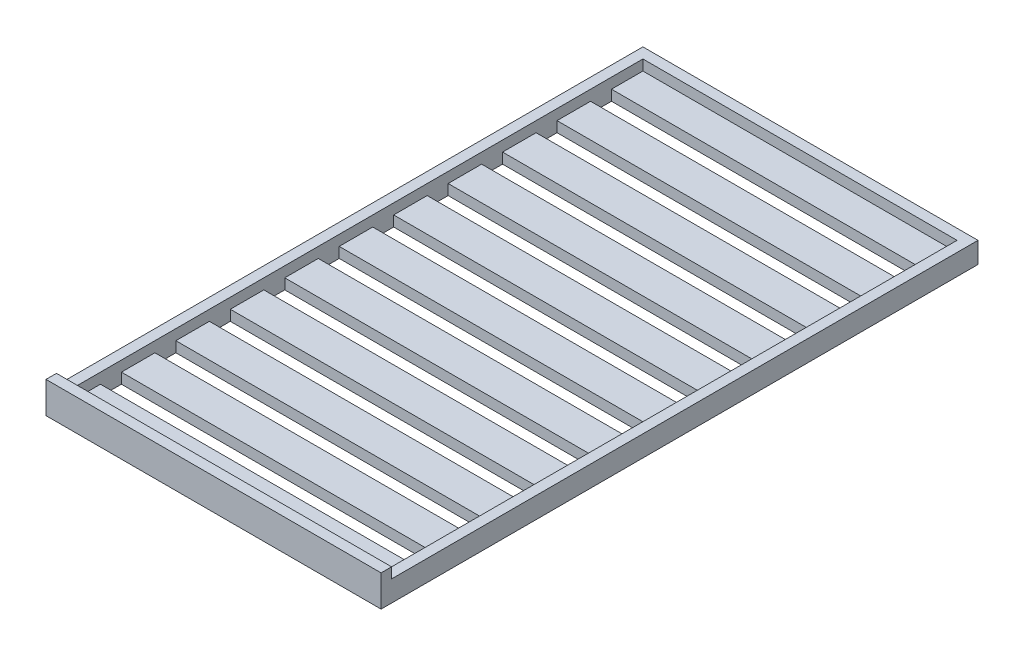
SolidWorks part; units mm, degrees
ref_plane "Front Plane" through (0, 0, 0) normal (0, 0, 1) x (1, 0, 0)
ref_plane "Top Plane" through (0, 0, 0) normal (0, 1, 0) x (1, 0, 0)
ref_plane "Right Plane" through (0, 0, 0) normal (1, 0, 0) x (0, 0, -1)
sketch "Tray" plane through (0, 0, 0) normal (0, 1, 0) x (1, 0, 0)
  line L1 (-80, 135) -> (80, 135)
  line L2 (-80, 135) -> (-80, -150)
  line L3 (-80, -150) -> (80, -150)
  line L4 (80, 135) -> (80, -150)
  dimension "D1" = 160
  dimension "D2" = 80
  dimension "D3" = 150
  dimension "D4" = 285
extrude "Boss-Extrude1" add sketch "Tray" along normal blind 5
sketch "tray frame" plane through (0, 5, 0) normal (0, 1, 0) x (1, 0, 0)
  line L0 (-80, -145) -> (-75, -145)
  line L1 (-75, -145) -> (-75, 130)
  line L2 (-75, 130) -> (75, 130)
  line L3 (75, 130) -> (75, -145)
  line L4 (75, -145) -> (80, -145)
  line L5 (80, -145) -> (80, 135)
  line L6 (80, 135) -> (-80, 135)
  line L7 (-80, 135) -> (-80, -145)
  line L8 (80, 135) -> (-80, 135) construction
  line L9 (80, -150) -> (80, 135) construction
  line L10 (-80, 135) -> (-80, -150) construction
  dimension "D1" = 5
  dimension "D2" = 5
  dimension "D3" = 5
  dimension "D4" = 280
extrude "Boss-Extrude2" add sketch "tray frame" along normal blind 5
sketch "Sketch3" plane through (0, 5, 0) normal (0, 1, 0) x (1, 0, 0)
  line L0 (-80, -150) -> (80, -150) construction
  line L1 (-80, -145) -> (80, -145)
  line L2 (-80, -145) -> (-80, -150)
  line L3 (-80, -150) -> (80, -150)
  line L4 (80, -145) -> (80, -150)
  line L5 (-80, -145) -> (-80, -150) construction
  line L6 (80, -150) -> (80, -145) construction
  line L7 (-80, -145) -> (-75, -145) construction
extrude "Boss-Extrude3" add sketch "Sketch3" along normal blind 10
sketch "Sketch4" plane through (0, 5, 0) normal (0, 1, 0) x (1, 0, 0)
  line L0 (75, -145) -> (-75, -145) construction
  line L1 (-75, 115) -> (75, 115)
  line L2 (-75, 115) -> (-75, 105)
  line L3 (-75, 105) -> (75, 105)
  line L4 (75, 115) -> (75, 105)
  line L5 (-75, 89) -> (75, 89)
  line L6 (-75, 89) -> (-75, 79)
  line L7 (-75, 79) -> (75, 79)
  line L8 (75, 89) -> (75, 79)
  line L9 (-75, 37) -> (75, 37)
  line L10 (-75, 37) -> (-75, 27)
  line L11 (-75, 27) -> (75, 27)
  line L12 (75, 37) -> (75, 27)
  line L13 (-75, 11) -> (75, 11)
  line L14 (-75, 11) -> (-75, 1)
  line L15 (-75, 1) -> (75, 1)
  line L16 (75, 11) -> (75, 1)
  line L17 (-75, -25) -> (75, -25)
  line L18 (-75, -25) -> (-75, -15)
  line L19 (-75, -15) -> (75, -15)
  line L20 (75, -25) -> (75, -15)
  line L21 (-75, -41) -> (75, -41)
  line L22 (-75, -41) -> (-75, -51)
  line L23 (-75, -51) -> (75, -51)
  line L24 (75, -41) -> (75, -51)
  line L25 (-75, -67) -> (75, -67)
  line L26 (-75, -67) -> (-75, -77)
  line L27 (-75, -77) -> (75, -77)
  line L28 (75, -67) -> (75, -77)
  line L29 (-75, -93) -> (75, -93)
  line L30 (-75, -93) -> (-75, -103)
  line L31 (-75, -103) -> (75, -103)
  line L32 (75, -93) -> (75, -103)
  line L33 (-75, -119) -> (75, -119)
  line L34 (-75, -119) -> (-75, -129)
  line L35 (-75, -129) -> (75, -129)
  line L36 (75, -119) -> (75, -129)
  line L37 (-75, 63) -> (75, 63)
  line L38 (-75, 63) -> (-75, 53)
  line L39 (-75, 53) -> (75, 53)
  line L40 (75, 63) -> (75, 53)
  line L44 (75, 130) -> (75, -145) construction
  line L45 (-75, -145) -> (-75, 130) construction
  dimension "D1" = 10
  dimension "D2" = 16
  dimension "D3" = 16
  dimension "D4" = 16
  dimension "D5" = 16
  dimension "D6" = 16
  dimension "D7" = 16
  dimension "D8" = 16
  dimension "D9" = 16
  dimension "D10" = 16
  dimension "D11" = 16
extrude "Cut-Extrude1" cut sketch "Sketch4" against normal through all
